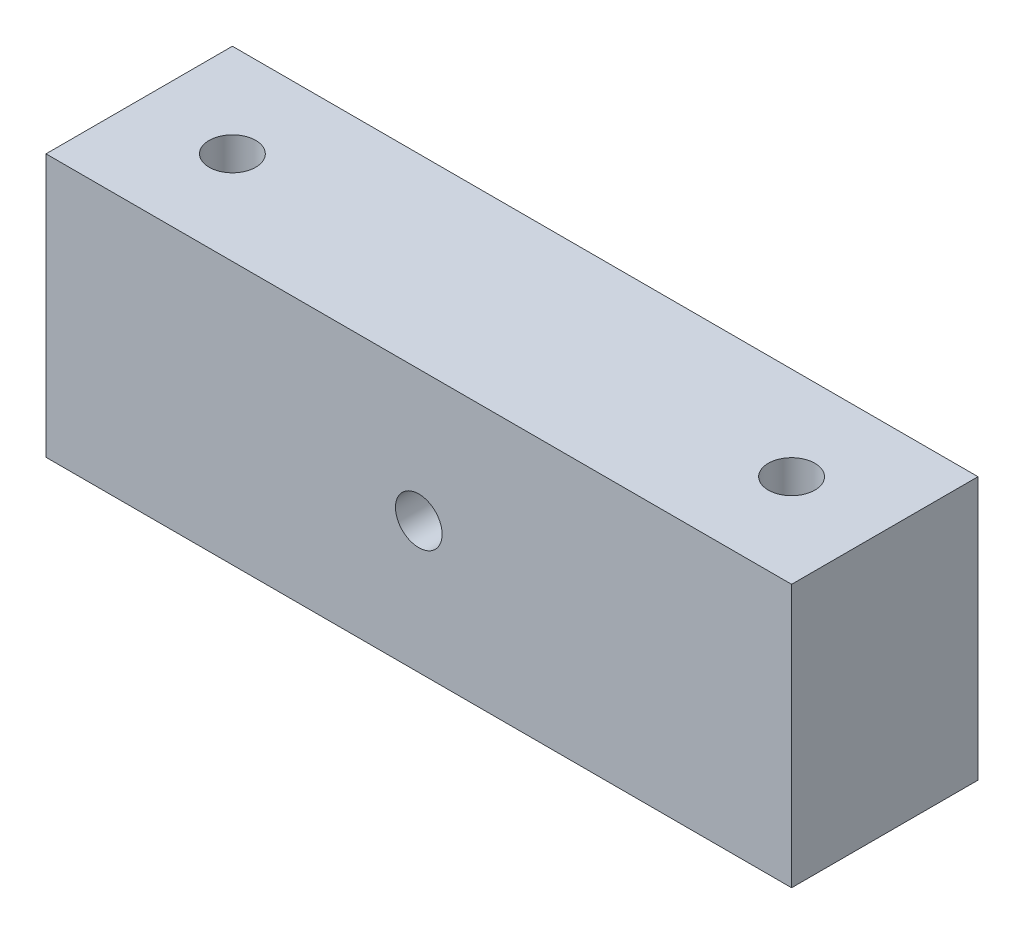
SolidWorks part; units mm, degrees
material "Copper"
ref_plane "Front Plane" through (0, 0, 0) normal (0, 0, 1) x (1, 0, 0)
ref_plane "Top Plane" through (0, 0, 0) normal (0, 1, 0) x (1, 0, 0)
ref_plane "Right Plane" through (0, 0, 0) normal (1, 0, 0) x (0, 0, -1)
sketch "Sketch1" plane through (0, 0, 0) normal (0, 1, 0) x (1, 0, 0)
  line L0 (0, 5) -> (40, 5) construction
  line L1 (0, 0) -> (40, 0)
  line L2 (0, 0) -> (0, 10)
  line L3 (0, 10) -> (40, 10)
  line L4 (40, 0) -> (40, 10)
  line L5 (5, 5) -> (5, 10) construction
  line L6 (35, 10) -> (35, 5) construction
  dimension "D1" = 5
  dimension "D2" = 5
  dimension "D3" = 5
  dimension "D4" = 5
  dimension "D5" = 40
extrude "Boss-Extrude1" add sketch "Sketch1" along normal blind 14.1
sketch "Sketch2" plane through (0, 14.1, 0) normal (0, 1, 0) x (1, 0, 0)
  point P0 (35, 5)
  point P2 (5, 5)
hole_wizard "M3x0.5 Tapped Hole3" positions "3DSketch1" profile "Sketch3" tap size "M3x0.5" standard "ANSI Metric" end condition through all
sketch3d "3DSketch1"
  point P0 (5, 14.1, -5)
  point P3 (35, 14.1, -5)
sketch "Sketch3" plane through (5, 14.1, -5) normal (1, 0, 0) x (0, 0, 1)
  line L0 (0, 0) -> (0, 14.1)
  line L1 (0, 14.1) -> (1.25, 14.1)
  line L2 (1.25, 14.1) -> (1.25, 0)
  line L5 (1.25, 0) -> (0, 0)
  line L11 (0, -6.35) -> (0, 107.95) construction
  dimension "Thru Tap Drill Dia." = 2.5
  dimension "Thru Tap Drill Depth" = 14.1
cosmetic thread "Hole Thread1" parameters "D2"=3
cosmetic thread "Hole Thread2" parameters "D2"=3
sketch "Sketch4" plane through (0, 0, -10) normal (0, 0, -1) x (-1, 0, 0)
  line L0 (-40, 7.05) -> (0, 7.05)
  line L1 (-40, 14.1) -> (-40, 0) construction
  line L2 (0, 14.1) -> (0, 0) construction
hole_wizard "M3x0.5 Tapped Hole4" positions "3DSketch2" profile "Sketch5" tap size "M3x0.5" standard "ANSI Metric" end condition through all
sketch3d "3DSketch2"
  line L0 (40, 7.05, -10) -> (0, 7.05, -10) construction
  point P0 (20, 7.05, -10)
cosmetic thread "Hole Thread3" parameters "D2"=3
sketch "Sketch5" plane through (20, 7.05, -10) normal (1, 0, 0) x (0, 1, 0)
  line L0 (0, 0) -> (0, 10)
  line L1 (0, 10) -> (1.25, 10)
  line L2 (1.25, 10) -> (1.25, 0)
  line L5 (1.25, 0) -> (0, 0)
  line L11 (0, -6.35) -> (0, 107.95) construction
  dimension "Thru Tap Drill Dia." = 2.5
  dimension "Thru Tap Drill Depth" = 10
equation "\"D2@Sketch1\"=\"D1@Sketch1\""
equation "\"D3@Sketch1\"=\"D1@Sketch1\""
